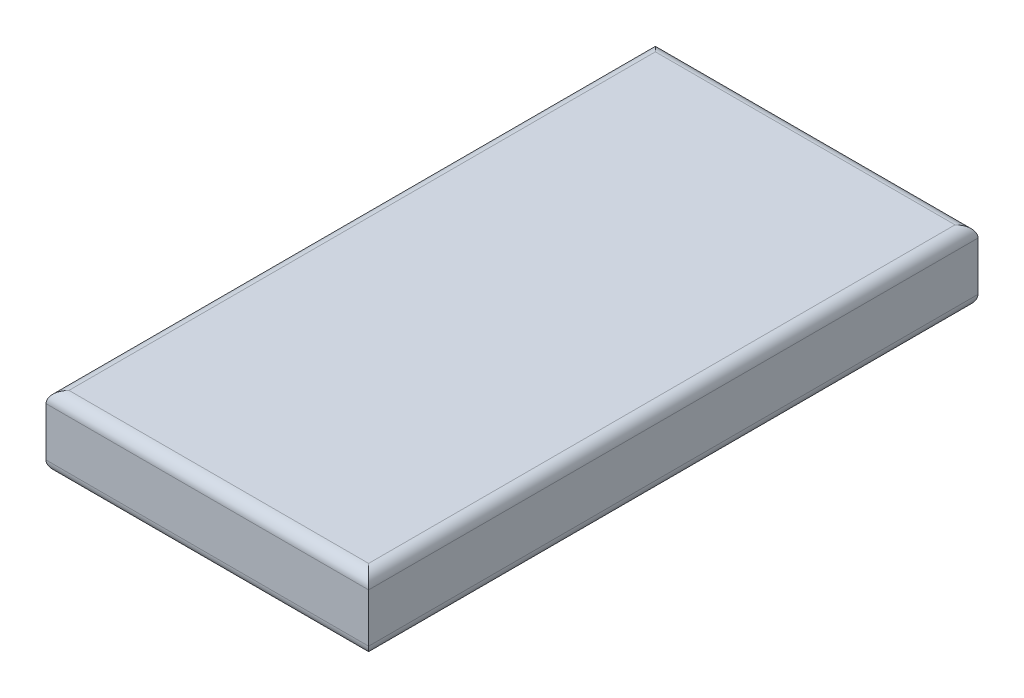
SolidWorks part; units mm, degrees
material "1060 Alloy"
ref_plane "Front Plane" through (0, 0, 0) normal (0, 0, 1) x (1, 0, 0)
ref_plane "Top Plane" through (0, 0, 0) normal (0, 1, 0) x (1, 0, 0)
ref_plane "Right Plane" through (0, 0, 0) normal (1, 0, 0) x (0, 0, -1)
sketch "Sketch1" plane through (0, 0, 0) normal (0, 1, 0) x (1, 0, 0)
  line L1 (0, 0) -> (-14.2875, 0)
  line L2 (0, 0) -> (0, 26.9875)
  line L3 (0, 26.9875) -> (-14.2875, 26.9875)
  line L4 (-14.2875, 0) -> (-14.2875, 26.9875)
  dimension "D1" = 14.2875
  dimension "D2" = 26.9875
extrude "Boss-Extrude1" add sketch "Sketch1" along normal blind 3.175
fillet "Fillet1" radius 0.508 8 edges at (-7.1437, 0, -26.9875) (-14.2875, 0, -13.4937) (-7.1437, 0, 0) (0, 0, -13.4937) (-7.1437, 3.175, 0) (-14.2875, 3.175, -13.4937) (-7.1437, 3.175, -26.9875) (0, 3.175, -13.4937)
